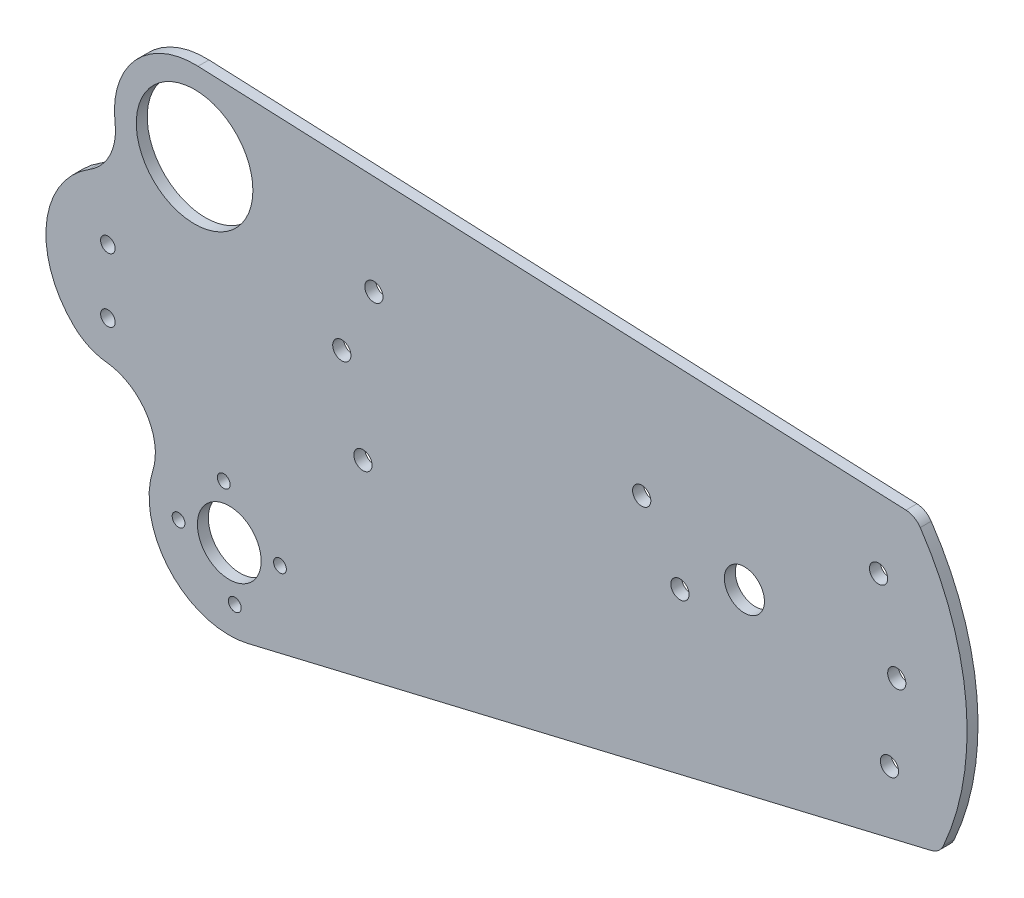
SolidWorks part; units mm, degrees
ref_plane "Front Plane" through (0, 0, 0) normal (0, 0, 1) x (1, 0, 0)
ref_plane "Top Plane" through (0, 0, 0) normal (0, 1, 0) x (1, 0, 0)
ref_plane "Right Plane" through (0, 0, 0) normal (1, 0, 0) x (0, 0, -1)
sketch "Sketch1" plane through (0, 0, 0) normal (0, 0, 1) x (1, 0, 0)
  line L0 (83.305, -33.5) -> (-137.2004, -33.5) construction
  line L1 (-113.5603, 49.4797) -> (80.7216, 41.1353)
  line L2 (-116.9253, 49.6243) -> (-102.5652, -81.605) construction
  line L3 (-99.3111, -80.7362) -> (92.6556, -29.4815) construction
  line L4 (75.1114, 41.3762) -> (83.1431, -32.0213) construction
  line L5 (-109.7453, -15.9904) -> (79.1273, 4.6775) construction
  line L6 (91, -33.5) -> (-88.5, -33.5) construction
  line L7 (-97.4673, 5.5) -> (-155.3054, 5.5) construction
  line L8 (-138.3, -14) -> (-155.3054, -14) construction
  line L9 (-138.3, 5.5) -> (-138.3, -33.5) construction
  line L10 (-155.3054, 5.5) -> (-155.3054, -33.5) construction
  line L11 (36.3824, 33.5) -> (36.3824, -33.5) construction
  line L12 (-111.8477, -83.7242) -> (87.5903, -36.3264)
  line L13 (-91.5, 33.5) -> (88, 33.5) construction
  line L14 (-68.3, -21.5) -> (-108.6591, -25.9164) construction
  circle A0 centre (36.3824, 0) radius 5.5
  circle A1 centre (-114.5043, 27.5) radius 14 construction
  circle A2 centre (-104.9862, -59.4808) radius 14 construction
  arc A3 (-91.5, 33.5) -> (-88.5, -33.5) centre (-18.0922, 3.2198) ccw construction
  circle A4 centre (-68.3, -21.5) radius 2.5
  circle A5 centre (-68.3, -21.5) radius 2.5 construction
  circle A6 centre (-138.3, -5.25) radius 2
  circle A7 centre (-138.3, -22.75) radius 2
  arc A8 (-143.371, 10.0569) -> (-147.5429, -29.3643) centre (-130.3054, -11.2571) ccw
  arc A9 (-147.5429, -29.3643) -> (-137.2004, -33.5) centre (-137.2004, -18.5) ccw
  circle A10 centre (-114.5043, 27.5) radius 22
  arc A11 (87.5903, -36.3264) -> (91, -33.5) centre (86.4343, -31.4619) ccw
  circle A12 centre (-104.9862, -59.4808) radius 22
  arc A13 (91, -33.5) -> (84.6484, 38.9414) centre (22.6589, -2.9929) ccw
  arc A14 (91, -33.5) -> (88, 33.5) centre (22.6589, -2.9929) ccw construction
  arc A15 (84.6484, 38.9414) -> (80.7216, 41.1353) centre (80.507, 36.1399) ccw
  arc A17 (-125.9657, -52.858) -> (-138.7351, -33.4213) centre (-140.2699, -48.3426) ccw
  arc A18 (-143.371, 10.0569) -> (-136.3295, 24.7324) centre (-151.2104, 22.8454) ccw
  circle A19 centre (-74.1, 1.7) radius 2.5
  circle A20 centre (-65.3, 20) radius 2.5
  circle A21 centre (8.2, 8.3) radius 2.5
  circle A23 centre (18.7, -8.7) radius 2.5
  circle A25 centre (78.2, -0.1) radius 2.5
  circle A26 centre (76.2, -22) radius 2.5
  circle A27 centre (73.2, 22.3) radius 2.5
  circle A28 centre (73.2, 22.3) radius 2.5 construction
  circle A29 centre (78.2, -0.1) radius 2.5 construction
  circle A31 centre (8.2, 8.3) radius 2.5 construction
  circle A32 centre (18.7, -8.7) radius 2.5 construction
  circle A33 centre (76.2, -22) radius 2.5 construction
  circle A34 centre (-74.1, 1.7) radius 2.5 construction
  circle A35 centre (-65.3, 20) radius 2.5 construction
  circle A36 centre (-116.0272, 41.4169) radius 1.75
  circle A37 centre (-100.5874, 29.0229) radius 1.75
  circle A38 centre (-112.9814, 13.5831) radius 1.75
  circle A39 centre (-128.4212, 25.9771) radius 1.75
  circle A40 centre (-106.5091, -45.5639) radius 1.75
  circle A41 centre (-91.0693, -57.9579) radius 1.75
  circle A42 centre (-103.4633, -73.3977) radius 1.75
  circle A43 centre (-118.9031, -61.0037) radius 1.75
  circle A44 centre (36.3824, 0) radius 35 construction
  circle A45 centre (36.3824, 0) radius 43
  circle A49 centre (-104.9862, -59.4808) radius 16
  circle A50 centre (-114.5043, 27.5) radius 16
  circle A51 centre (-114.5043, 27.5) radius 8.75
  circle A52 centre (-104.9862, -59.4808) radius 8.75
  arc A53 (91, -33.5) -> (88, 33.5) centre (22.6589, -2.9929) ccw construction
  point P52 (79.1273, 4.6775)
  point P109 (-114.5043, 27.5)
  point P118 (-104.9862, -59.4808)
  dimension "D5" = 4
  dimension "D6" = 25
  dimension "D9" = 15
  dimension "D13" = 10
  dimension "D14" = 28
  dimension "D11" = 44
  dimension "D15" = 3.5
  dimension "D12" = 70
  dimension "D19" = 11
  dimension "D20" = 17.5
  dimension "D22" = 32
  dimension "D2" = 39
  dimension "D3" = 70
  dimension "D4" = 17.5
  dimension "D7" = 14
  dimension "D8" = 10
  dimension "D10" = 87.5
  dimension "D21" = 190
  dimension "D23" = 40.6
  dimension "D18" = 8
  dimension "D16" = 4
  dimension "D17" = 4
extrude "Boss-Extrude1" add sketch "Sketch1" along normal blind 3
